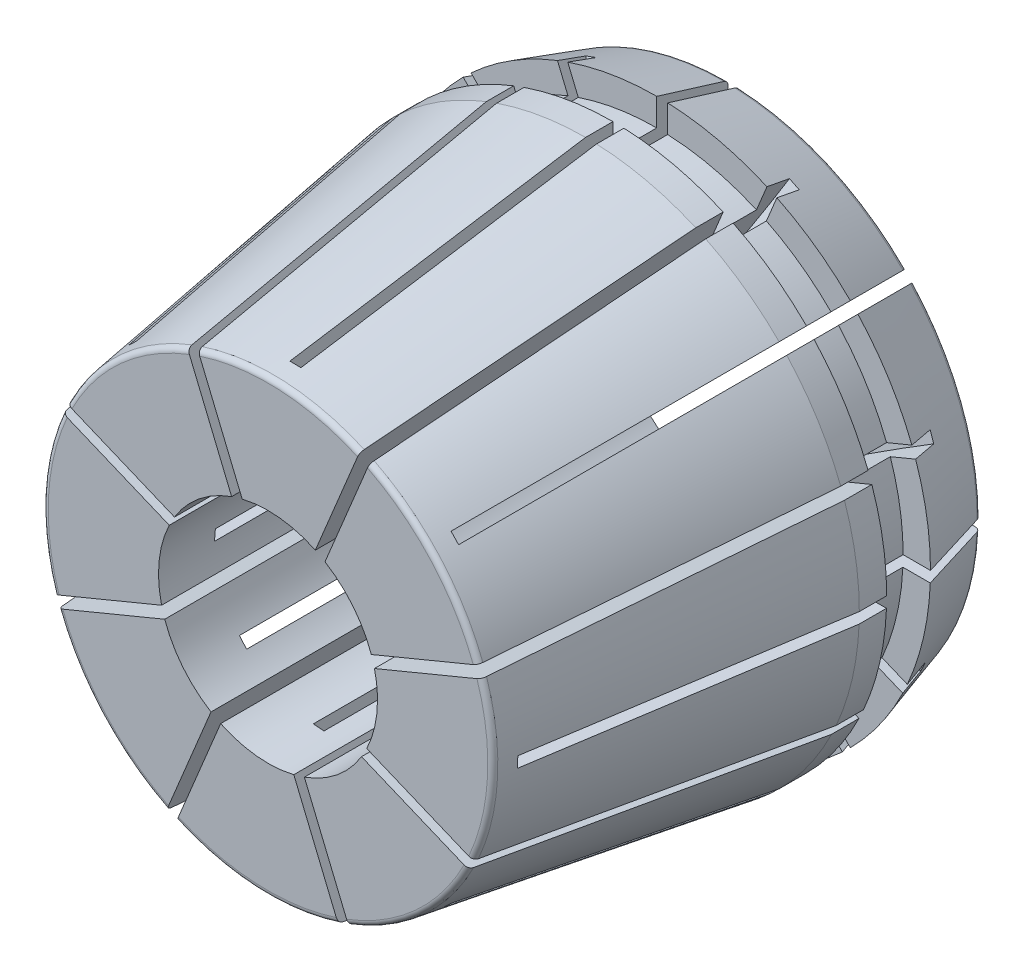
SolidWorks part; units mm, degrees
ref_plane "Front Plane" through (0, 0, 0) normal (0, 0, 1) x (1, 0, 0)
ref_plane "Top Plane" through (0, 0, 0) normal (0, 1, 0) x (1, 0, 0)
ref_plane "Right Plane" through (0, 0, 0) normal (1, 0, 0) x (0, 0, -1)
sketch "Sketch1" plane through (0, 0, 0) normal (0, 1, 0) x (1, 0, 0)
  line L0 (0, 58) -> (0, 100) construction
  line L1 (23, 100) -> (10, 100)
  line L2 (23, 100) -> (25, 93.5)
  line L3 (25, 93.5) -> (22.5, 93.5)
  line L4 (22.5, 93.5) -> (22.5, 89.5)
  line L5 (22.5, 89.5) -> (25, 89.5)
  line L6 (25, 89.5) -> (25, 87)
  line L7 (25, 87) -> (20.5, 58)
  line L8 (20.5, 58) -> (10, 58)
  line L9 (10, 100) -> (10, 58)
  dimension "D3" = 4
  dimension "D4" = 2.5
  dimension "D9" = 2.5
  dimension "D8" = 6.5
  dimension "D2" = 10
  dimension "D1" = 42
  dimension "D5" = 72.897
  dimension "D7" = 25
revolve "Revolve1" add sketch "Sketch1" angle 360 about L0
fillet "Fillet1" radius 0.5 1 edges at (23, 0, -100)
fillet "Fillet2" radius 0.5 1 edges at (20.5, 0, -58)
sketch "Sketch2" plane through (0, 0, 0) normal (1, 0, 0) x (0, 0, -1)
  line L1 (81, 0) -> (102, 0)
  line L5 (102, 0) -> (102, -21)
  arc A0 (81, 0) -> (102, -21) centre (81, -21) ccw
  point P6 (0, 0)
  point P9 (0, 0)
  point P10 (0, 0)
  point P11 (0, 0)
  dimension "D1" = 21
extrude "Cut-Extrude1" cut sketch "Sketch2" against normal blind 1
pattern_circular "CirPattern1" count 8 over 360 about axis through (0, 0, 0) along (0, 0, 1) of "Cut-Extrude1"
ref_plane "Plane1" through (0.2071, -0.5, 0) normal (-0.3827, 0.9239, 0) x (0.9239, 0.3827, 0)
sketch "Sketch4" plane through (0.2071, -0.5, 0) normal (-0.3827, 0.9239, 0) x (0.9239, 0.3827, 0)
  line L0 (22.6307, 100) -> (-22.6307, 100) construction
  line L1 (42.6742, 14.6516) -> (0, 14.6516)
  line L3 (0, 14.6516) -> (0, 57.3258)
  line L4 (0, 14.6516) -> (0, 57.3258)
  line L5 (22.6307, 100) -> (22.6307, 95)
  line L9 (0, 100) -> (22.6307, 100) construction
  arc A1 (42.6742, 14.6516) -> (0, 57.3258) centre (42.6742, 57.3258) ccw
  point P10 (22.6307, 100)
  dimension "D1" = 5
extrude "Cut-Extrude3" cut sketch "Sketch4" against normal blind 1
pattern_circular "CirPattern2" count 8 over 360 about axis through (0, 0, 0) along (0, 0, 1) of "Cut-Extrude3"
equation "\"colletheight\" = 42"
equation "\"slotdiam.offset\"= \"colletheight\" / 2"
equation "\"vial diam\"= 20"
equation "\"D2@Sketch1\"=\"vial diam\"/2"
equation "\"D1@Sketch1\"=\"colletheight\""
equation "\"D1@Sketch2\"=\"slotdiam.offset\""
